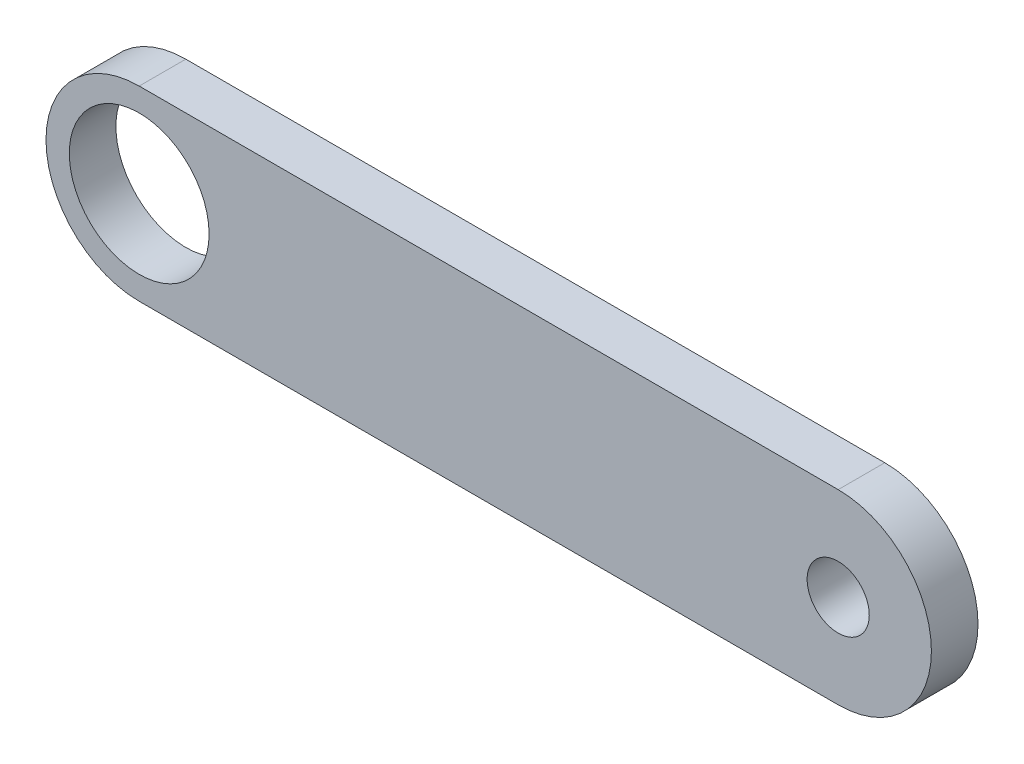
SolidWorks part; units mm, degrees
ref_plane "前视基准面" through (0, 0, 0) normal (0, 0, 1) x (1, 0, 0)
ref_plane "上视基准面" through (0, 0, 0) normal (0, 1, 0) x (1, 0, 0)
ref_plane "右视基准面" through (0, 0, 0) normal (1, 0, 0) x (0, 0, -1)
sketch "草图1" plane through (0, 0, 0) normal (0, 0, 1) x (1, 0, 0)
  line L0 (0, 0) -> (45, 0) construction
  line L1 (0, 6) -> (45, 6)
  line L2 (0, -6) -> (45, -6)
  arc A0 (0, 6) -> (0, -6) centre (0, 0) ccw
  arc A1 (45, -6) -> (45, 6) centre (45, 0) ccw
  circle A2 centre (0, 0) radius 4.5
  circle A3 centre (45, 0) radius 2
  point P3 (22.5, 0)
  dimension "D3" = 9
  dimension "D4" = 4
  dimension "D1" = 45
  dimension "D2" = 12
extrude "凸台-拉伸1" add sketch "草图1" along normal blind 3
